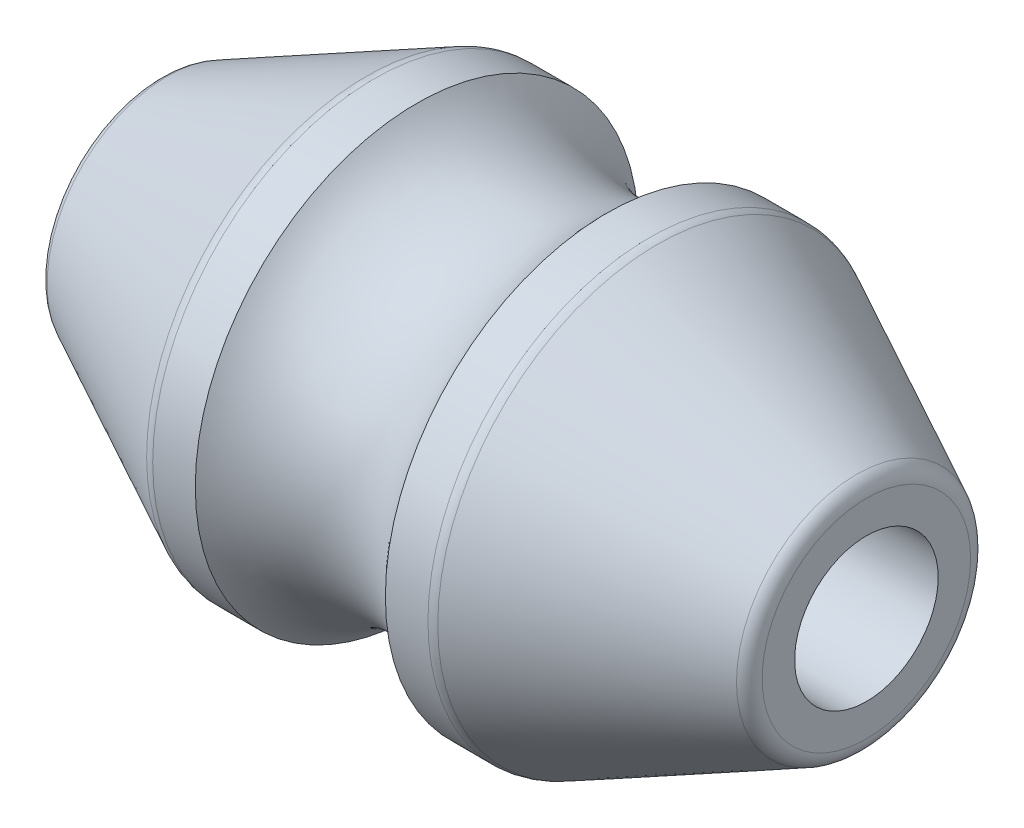
SolidWorks part; units mm, degrees
ref_plane "Alzado" through (0, 0, 0) normal (1, 0, 0) x (0, 1, 0)
ref_plane "Planta" through (0, 0, 0) normal (0, 0, 1) x (0, 1, 0)
ref_plane "Vista lateral" through (0, 0, 0) normal (0, 1, 0) x (-1, 0, 0)
sketch "Croquis1" plane through (0, 0, 0) normal (1, 0, 0) x (0, 1, 0)
  circle A0 centre (0, 0) radius 12.5
  circle A1 centre (0, 0) radius 4.05
  dimension "D1" = 25
  dimension "D2" = 8.1
extrude "Saliente-Extruir1" add sketch "Croquis1" along normal mid plane 40
sketch "Croquis2" plane through (0, 0, 0) normal (0, 1, 0) x (-1, 0, 0)
  line L0 (0, 17) -> (0, 14.0291) construction
  line L1 (-8.2753, 0) -> (8.2753, 0) construction
  circle A0 centre (0, 17) radius 7
  point P7 (0, 0)
  dimension "D1" = 14
  dimension "D2" = 17
revolve "Cortar-Revolución1" cut sketch "Croquis2" angle 360 about L1
chamfer "Chaflán1" distance 6 distance2 12 1 edges at (-20, 0, -12.5)
chamfer "Chaflán2" distance 12 distance2 6 1 edges at (20, 0, -12.5)
fillet "Redondeo1" radius 1 4 edges at (-20, 0, -6.5) (-8, 0, -12.5) (8, 0, -12.5) (20, 0, -6.5)
